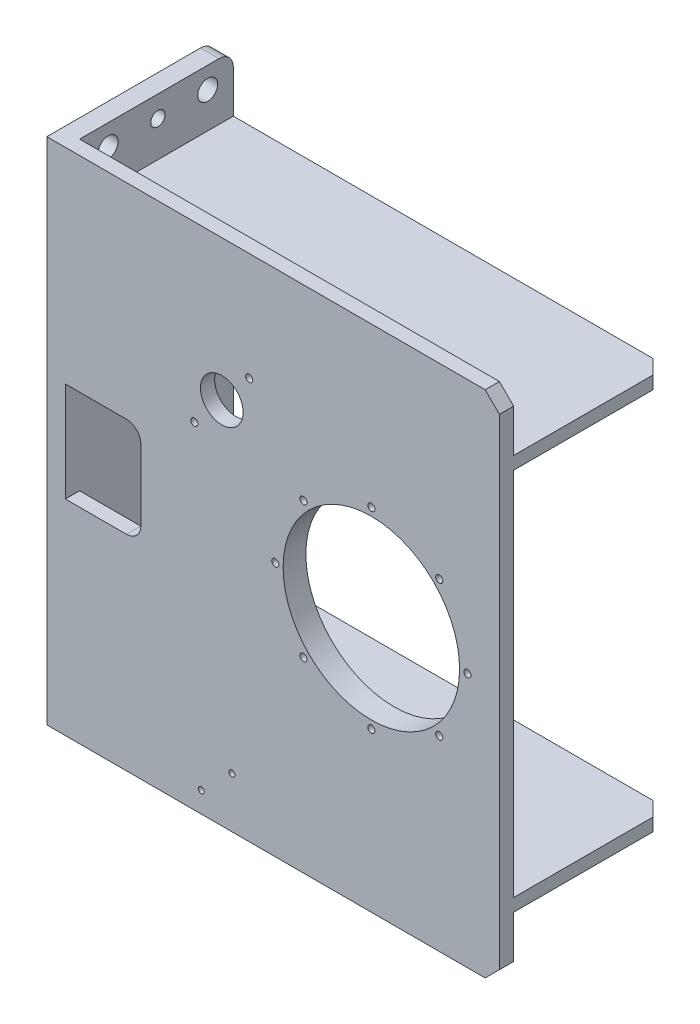
SolidWorks part; units mm, degrees
ref_plane "正面" through (0, 0, 0) normal (0, 0, 1) x (1, 0, 0)
ref_plane "平面" through (0, 0, 0) normal (0, 1, 0) x (1, 0, 0)
ref_plane "右側面" through (0, 0, 0) normal (1, 0, 0) x (0, 0, -1)
sketch "ｽｹｯﾁ1" plane through (0, 0, 0) normal (0, 0, 1) x (1, 0, 0)
  line L0 (13, 0) -> (308, 0)
  line L1 (308, 0) -> (318, 10)
  line L2 (318, 10) -> (318, 348)
  line L3 (318, 348) -> (308, 358)
  line L4 (308, 358) -> (13, 358)
  line L5 (13, 358) -> (13, 214)
  line L6 (13, 214) -> (56, 214)
  line L7 (66, 204) -> (66, 154)
  line L8 (56, 144) -> (13, 144)
  line L9 (13, 144) -> (13, 0)
  arc A0 (56, 214) -> (66, 204) centre (56, 204) cw
  arc A1 (66, 154) -> (56, 144) centre (56, 154) cw
extrude "ﾎﾞｽ - 押し出し1" add sketch "ｽｹｯﾁ1" against normal blind 10
sketch "ｽｹｯﾁ2" plane through (0, 0, 0) normal (1, 0, 0) x (0, 0, -1)
  line L0 (0, 0) -> (108, 0)
  line L1 (118, 10) -> (118, 348)
  line L2 (108, 358) -> (0, 358)
  line L3 (0, 358) -> (0, 0)
  arc A0 (108, 0) -> (118, 10) centre (108, 10) ccw
  arc A1 (118, 348) -> (108, 358) centre (108, 348) ccw
extrude "ﾎﾞｽ - 押し出し2" add sketch "ｽｹｯﾁ2" along normal blind 13
ref_plane "平面1" through (0, 40, 0) normal (0, 1, 0) x (1, 0, 0)
sketch "ｽｹｯﾁ4" plane through (0, 40, 0) normal (0, 1, 0) x (1, 0, 0)
  line L0 (13, 10) -> (318, 10)
  line L1 (318, 10) -> (318, 108)
  line L2 (318, 108) -> (308, 118)
  line L3 (308, 118) -> (13, 118)
  line L4 (13, 118) -> (13, 10)
extrude "ﾎﾞｽ - 押し出し3" add sketch "ｽｹｯﾁ4" along normal blind 9
ref_plane "平面2" through (0, 309, 0) normal (0, 1, 0) x (1, 0, 0)
sketch "ｽｹｯﾁ6" plane through (0, 309, 0) normal (0, 1, 0) x (1, 0, 0)
  line L0 (13, 10) -> (318, 10)
  line L1 (318, 10) -> (318, 108)
  line L2 (318, 108) -> (308, 118)
  line L3 (308, 118) -> (13, 118)
  line L4 (13, 118) -> (13, 10)
extrude "ﾎﾞｽ - 押し出し4" add sketch "ｽｹｯﾁ6" along normal blind 9
sketch "ｽｹｯﾁ7" plane through (0, 0, 0) normal (0, 0, 1) x (1, 0, 0)
  circle A0 centre (228, 179) radius 74.5
  circle A1 centre (228, 179) radius 62
extrude "ﾎﾞｽ - 押し出し5" add sketch "ｽｹｯﾁ7" against normal blind 16
sketch "ｽｹｯﾁ8" plane through (0, 0, 0) normal (0, 0, 1) x (1, 0, 0)
  circle A0 centre (228, 179) radius 62
extrude "ｶｯﾄ - 押し出し1" cut sketch "ｽｹｯﾁ8" against normal blind 10
sketch "ｽｹｯﾁ9" plane through (0, 0, 0) normal (0, 0, 1) x (1, 0, 0)
  circle A0 centre (122.891, 259.0915) radius 15
extrude "ｶｯﾄ - 押し出し2" cut sketch "ｽｹｯﾁ9" against normal blind 10
sketch "ｽｹｯﾁ10" plane through (0, 0, 0) normal (0, 0, 1) x (1, 0, 0)
  circle A0 centre (103.6074, 236.1102) radius 2.5
  circle A1 centre (142.1746, 282.0728) radius 2.5
extrude "ｶｯﾄ - 押し出し3" cut sketch "ｽｹｯﾁ10" against normal blind 10
sketch "ｽｹｯﾁ11" plane through (0, 0, 0) normal (0, 0, 1) x (1, 0, 0)
  circle A0 centre (108.5, 14.5) radius 2.1
  circle A1 centre (130, 35.5) radius 2.1
extrude "ｶｯﾄ - 押し出し4" cut sketch "ｽｹｯﾁ11" against normal blind 10
sketch "ｽｹｯﾁ12" plane through (0, 0, 0) normal (0, 0, 1) x (1, 0, 0)
  circle A0 centre (295.5, 179) radius 2.5
  circle A1 centre (275.7297, 226.7297) radius 2.5
  circle A2 centre (228, 246.5) radius 2.5
  circle A3 centre (180.2703, 226.7297) radius 2.5
  circle A4 centre (160.5, 179) radius 2.5
  circle A5 centre (180.2703, 131.2703) radius 2.5
  circle A6 centre (228, 111.5) radius 2.5
  circle A7 centre (275.7297, 131.2703) radius 2.5
extrude "ｶｯﾄ - 押し出し5" cut sketch "ｽｹｯﾁ12" against normal blind 16
sketch "ｽｹｯﾁ13" plane through (0, 0, 0) normal (1, 0, 0) x (0, 0, -1)
  circle A0 centre (30, 15) radius 7
  circle A1 centre (100, 15) radius 7
  circle A2 centre (30, 343) radius 7
  circle A3 centre (100, 343) radius 7
  circle A4 centre (100, 123) radius 7
  circle A5 centre (100, 235) radius 7
sketch "ｽｹｯﾁ14" plane through (0, 0, 0) normal (1, 0, 0) x (0, 0, -1)
  circle A0 centre (30, 15) radius 7
  circle A1 centre (100, 15) radius 7
  circle A2 centre (30, 343) radius 7
  circle A3 centre (100, 343) radius 7
  circle A4 centre (100, 123) radius 7
  circle A5 centre (100, 235) radius 7
extrude "ｶｯﾄ - 押し出し7" cut sketch "ｽｹｯﾁ14" along normal blind 13
sketch "ｽｹｯﾁ15" plane through (0, 0, 0) normal (1, 0, 0) x (0, 0, -1)
  circle A0 centre (65, 15) radius 5
  circle A1 centre (65, 343) radius 5
sketch "ｽｹｯﾁ16" plane through (0, 0, 0) normal (1, 0, 0) x (0, 0, -1)
  circle A0 centre (65, 15) radius 5
  circle A1 centre (65, 343) radius 5
extrude "ｶｯﾄ - 押し出し9" cut sketch "ｽｹｯﾁ16" along normal blind 13
